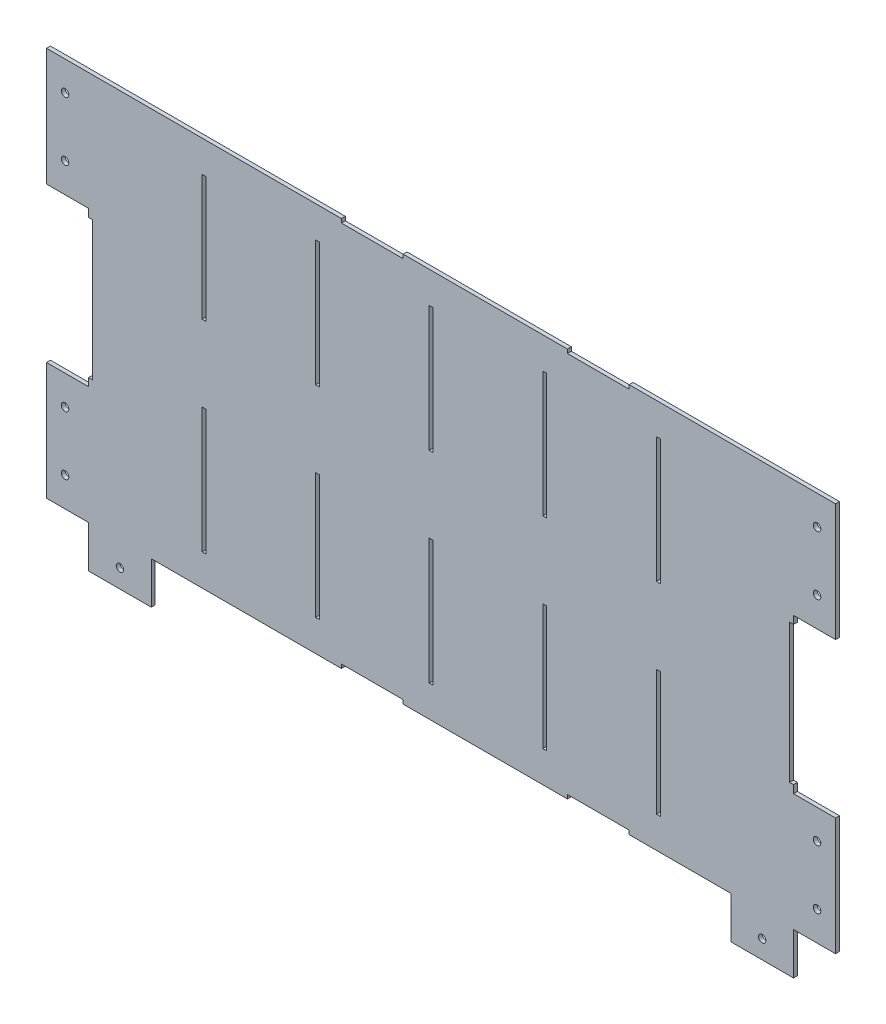
SolidWorks part; units mm, degrees
material "6061-T6 (SS)"
ref_plane "X-Y Datum" through (0, 0, 0) normal (0, 0, 1) x (1, 0, 0)
ref_plane "X-Z Datum" through (0, 0, 0) normal (0, 1, 0) x (1, 0, 0)
ref_plane "Y-Z Datum" through (0, 0, 0) normal (1, 0, 0) x (0, 0, -1)
sketch "Sketch1" plane through (0, 0, 0) normal (0, 0, 1) x (1, 0, 0)
  line L0 (-285.4305, 0) -> (285.4305, 0) construction
  line L1 (-285.4305, -157.7875) -> (285.4305, -157.7875)
  line L2 (-285.4305, -157.7875) -> (-285.4305, 157.7875)
  line L3 (-285.4305, 157.7875) -> (285.4305, 157.7875)
  line L4 (285.4305, -157.7875) -> (285.4305, 157.7875)
  line L5 (-285.4305, -157.7875) -> (285.4305, 157.7875) construction
  line L6 (-285.4305, 157.7875) -> (285.4305, -157.7875) construction
  line L7 (-282.2555, -154.615) -> (-282.2555, 154.615)
  line L8 (-280.6655, -153.025) -> (-195.0655, -153.025)
  line L9 (-280.6655, -153.025) -> (-280.6655, 153.025)
  line L10 (-280.6655, 153.025) -> (-195.0655, 153.025)
  line L11 (-195.0655, -153.025) -> (-195.0655, 153.025)
  line L12 (-280.6655, -153.025) -> (-195.0655, 153.025) construction
  line L13 (-280.6655, 153.025) -> (-195.0655, -153.025) construction
  line L14 (-282.2555, 154.615) -> (-193.4755, 154.615)
  line L15 (-193.4755, -154.615) -> (-193.4755, 154.615)
  line L16 (-282.2555, -154.615) -> (-193.4755, -154.615)
  line L17 (-190.3005, 154.615) -> (-101.5205, 154.615)
  line L18 (-188.7105, 153.025) -> (-103.1105, 153.025)
  line L19 (-190.3005, -154.615) -> (-190.3005, 154.615)
  line L20 (-188.7105, -153.025) -> (-188.7105, 153.025)
  line L21 (-101.5205, -154.615) -> (-101.5205, 154.615)
  line L22 (-103.1105, -153.025) -> (-103.1105, 153.025)
  line L23 (-188.7105, -153.025) -> (-103.1105, -153.025)
  line L24 (-190.3005, -154.615) -> (-101.5205, -154.615)
  line L25 (-188.7105, -153.025) -> (-103.1105, 153.025) construction
  line L26 (-188.7105, 153.025) -> (-103.1105, -153.025) construction
  line L27 (-98.3455, 154.615) -> (-9.5655, 154.615)
  line L28 (-96.7555, 153.025) -> (-11.1555, 153.025)
  line L29 (-98.3455, -154.615) -> (-98.3455, 154.615)
  line L30 (-96.7555, -153.025) -> (-96.7555, 153.025)
  line L31 (-9.5655, -154.615) -> (-9.5655, 154.615)
  line L32 (-11.1555, -153.025) -> (-11.1555, 153.025)
  line L33 (-96.7555, -153.025) -> (-11.1555, -153.025)
  line L34 (-98.3455, -154.615) -> (-9.5655, -154.615)
  line L35 (-96.7555, -153.025) -> (-11.1555, 153.025) construction
  line L36 (-96.7555, 153.025) -> (-11.1555, -153.025) construction
  line L37 (-6.3905, 154.615) -> (82.3895, 154.615)
  line L38 (-4.8005, 153.025) -> (80.7995, 153.025)
  line L39 (-6.3905, -154.615) -> (-6.3905, 154.615)
  line L40 (-4.8005, -153.025) -> (-4.8005, 153.025)
  line L41 (82.3895, -154.615) -> (82.3895, 154.615)
  line L42 (80.7995, -153.025) -> (80.7995, 153.025)
  line L43 (-4.8005, -153.025) -> (80.7995, -153.025)
  line L44 (-6.3905, -154.615) -> (82.3895, -154.615)
  line L45 (-4.8005, -153.025) -> (80.7995, 153.025) construction
  line L46 (-4.8005, 153.025) -> (80.7995, -153.025) construction
  line L47 (85.5645, 154.615) -> (174.3445, 154.615)
  line L48 (87.1545, 153.025) -> (172.7545, 153.025)
  line L49 (85.5645, -154.615) -> (85.5645, 154.615)
  line L50 (87.1545, -153.025) -> (87.1545, 153.025)
  line L51 (174.3445, -154.615) -> (174.3445, 154.615)
  line L52 (172.7545, -153.025) -> (172.7545, 153.025)
  line L53 (87.1545, -153.025) -> (172.7545, -153.025)
  line L54 (85.5645, -154.615) -> (174.3445, -154.615)
  line L55 (87.1545, -153.025) -> (172.7545, 153.025) construction
  line L56 (87.1545, 153.025) -> (172.7545, -153.025) construction
  point P0 (0, 0)
  point P8 (-237.8655, 0)
  point P17 (-145.9105, 0)
  dimension "D1" = 570.861
  dimension "D2" = 315.575
  dimension "D3" = 306.05
  dimension "D4" = 85.6
  dimension "D5" = 3.175
  dimension "D8" = 3.175
  dimension "D9" = 91.955
  dimension "D6" = 1.59
  dimension "D7" = 5
extrude "Boss-Extrude1" add sketch "Sketch1" along normal blind 3.175
sketch "Sketch2" plane through (0, 0, 3.175) normal (0, 0, 1) x (1, 0, 0)
  line L0 (-190.3005, -154.615) -> (-193.4755, -154.615) construction
  line L1 (-191.888, -154.615) -> (-191.888, 157.7875) construction
  line L2 (-285.4305, 157.7875) -> (285.4305, 157.7875) construction
  line L4 (-193.4755, -30.7875) -> (-190.3005, -30.7875)
  line L5 (-193.4755, -30.7875) -> (-193.4755, -132.3875)
  line L6 (-193.4755, -132.3875) -> (-190.3005, -132.3875)
  line L7 (-190.3005, -30.7875) -> (-190.3005, -132.3875)
  line L8 (-193.4755, -30.7875) -> (-190.3005, -132.3875) construction
  line L9 (-193.4755, -132.3875) -> (-190.3005, -30.7875) construction
  line L12 (-285.4305, -157.7875) -> (285.4305, -157.7875) construction
  point P8 (-191.888, -81.5875)
  dimension "D1" = 76.2
  dimension "D2" = 3.175
  dimension "D3" = 101.6
extrude "Cut-Extrude1" cut sketch "Sketch2" against normal blind 3.175
sketch "Sketch7" plane through (0, 0, 3.175) normal (0, 0, 1) x (1, 0, 0)
  line L0 (285.4305, -157.7875) -> (285.4305, 157.7875) construction
  line L1 (102.3049, -154.6125) -> (152.3049, -154.6125)
  line L2 (102.3049, -154.6125) -> (102.3049, -157.7875)
  line L3 (102.3049, -157.7875) -> (152.3049, -157.7875)
  line L4 (152.3049, -154.6125) -> (152.3049, -157.7875)
  line L5 (-80.6951, -154.6125) -> (-30.6951, -154.6125)
  line L6 (-80.6951, -154.6125) -> (-80.6951, -157.7875)
  line L7 (-80.6951, -157.7875) -> (-30.6951, -157.7875)
  line L8 (-30.6951, -154.6125) -> (-30.6951, -157.7875)
  dimension "D1" = 133
  dimension "D2" = 50
  dimension "D3" = 3.175
  dimension "D4" = 50
  dimension "D5" = 133.1256
extrude "Cut-Extrude5" cut sketch "Sketch7" against normal blind 3.175
mirror "Mirror3" about plane through (0, 0, 0) normal (0, 1, 0) of "Cut-Extrude1"
pattern_linear "LPattern2" count 5 spacing 91.96 along (1, 0, 0) of "Mirror3", "Cut-Extrude1"
sketch "Sketch9" plane through (0, 0, 0) normal (0, 0, -1) x (-1, 0, 0)
  line L0 (-304.4805, -62.5375) -> (-304.4805, -157.7875) construction
  line L9 (-285.4305, 157.7875) -> (-190.3024, 157.7875)
  line L10 (-285.4305, 157.7875) -> (-285.4305, 191.8235)
  line L11 (-285.4305, 191.8235) -> (-190.3024, 191.8235)
  line L12 (-190.3024, 157.7875) -> (-190.3024, 191.8235)
  line L13 (-285.4305, 157.7875) -> (-323.5305, 157.7875)
  line L14 (-285.4305, 157.7875) -> (-285.4305, 62.5375)
  line L15 (-285.4305, 62.5375) -> (-323.5305, 62.5375)
  line L18 (-323.5305, 110.1625) -> (-285.4305, 110.1625) construction
  line L20 (-285.4305, -157.7875) -> (-323.5305, -157.7875)
  line L26 (-285.4305, -62.5375) -> (-323.5305, -62.5375)
  line L28 (-323.5305, -106.9875) -> (-323.5305, -157.7875) construction
  line L29 (-323.5305, -106.9875) -> (-285.4305, -106.9875) construction
  line L30 (-304.4805, -62.5375) -> (-304.4805, -110.1625) construction
  line L31 (-304.4805, -110.1625) -> (-304.4805, -157.7875) construction
  line L32 (-304.4805, -62.5375) -> (-304.4805, -110.1625) construction
  line L33 (-304.4805, -110.1625) -> (-304.4805, -157.7875) construction
  line L35 (-323.5305, 62.5375) -> (-323.5305, 157.7875) construction
  line L36 (-319.4665, 157.7875) -> (-319.4665, 62.5375)
  line L37 (-323.5305, -62.5375) -> (-323.5305, -157.7875) construction
  line L40 (-304.4805, 157.7875) -> (-304.4805, 110.1625) construction
  line L41 (-304.4805, 110.1625) -> (-304.4805, 62.5375) construction
  line L42 (-319.4665, -62.5375) -> (-319.4665, -157.7875)
  line L43 (-304.4805, 110.1625) -> (-304.4805, 62.5375) construction
  line L44 (-304.4805, -62.5375) -> (-304.4805, -110.1625) construction
  line L45 (-304.4805, -110.1625) -> (-304.4805, -157.7875) construction
  line L46 (-285.4305, -62.5375) -> (-285.4305, -157.7875)
  line L47 (-285.4305, 176.8375) -> (-190.3024, 176.8375) construction
  line L48 (-285.4305, 176.8375) -> (-260.0305, 176.8375) construction
  line L49 (-234.6305, 191.8235) -> (-234.6305, 157.7875) construction
  line L50 (-285.4305, -176.8375) -> (-234.6305, -176.8375) construction
  line L51 (-285.4305, -157.7875) -> (-234.6305, -157.7875)
  line L52 (-285.4305, -157.7875) -> (-285.4305, -191.7755)
  line L53 (-285.4305, -191.7755) -> (-234.6305, -191.7755)
  line L54 (-234.6305, -157.7875) -> (-234.6305, -191.7755)
  circle A4 centre (-304.4805, 133.975) radius 3.048
  circle A6 centre (-304.4805, 86.35) radius 3.048
  circle A7 centre (-304.4805, -86.35) radius 3.048
  circle A8 centre (-304.4805, -133.975) radius 3.048
  circle A10 centre (-260.0305, 176.8375) radius 3.048
  circle A11 centre (-260.0305, -176.8375) radius 3
  point P22 (-307.5285, 133.975)
  point P39 (-260.0305, 179.8855)
  point P50 (-260.0305, -179.8375)
  dimension "D1" = 11.938
  dimension "D2" = 95.25
  dimension "D6" = 6.096
  dimension "D7" = 95.25
  dimension "D8" = 6.096
  dimension "D9" = 6.096
  dimension "D10" = 6.096
  dimension "D12" = 19.05
  dimension "D13" = 11.938
  dimension "D11" = 25.4
  dimension "D15" = 6
  dimension "D3" = 95.1281
  dimension "D4" = 34.036
  dimension "D5" = 19.05
  dimension "D14" = 25.4
  dimension "D16" = 19.05
  dimension "D17" = 11.938
  dimension "D18" = 50.8
  dimension "D19" = 25.4
extrude "Boss-Extrude3" add sketch "Sketch9" against normal blind 3.175
mirror "Mirror4" about plane through (0, 0, 0) normal (1, 0, 0) of "Boss-Extrude3"
mirror "Mirror5" about plane through (0, 0, 0) normal (0, 1, 0) of "Cut-Extrude5"
sketch "Sketch10" plane through (0, 0, 0) normal (0, 0, -1) x (-1, 0, 0)
  line L0 (-285.4305, 62.5375) -> (-285.4305, 56.1875)
  line L1 (-285.4305, -62.5375) -> (-285.4305, 62.5375) construction
  line L2 (-285.4305, -62.5375) -> (-319.4665, -62.5375) construction
  line L3 (-285.4305, 56.1875) -> (-282.2555, 56.1875)
  line L4 (-285.4305, 56.1875) -> (-285.4305, -56.1875)
  line L5 (-285.4305, -56.1875) -> (-282.2555, -56.1875)
  line L6 (-282.2555, 56.1875) -> (-282.2555, -56.1875)
  line L7 (-285.4305, 62.5375) -> (-319.4665, 62.5375) construction
  dimension "D1" = 6.35
  dimension "D2" = 3.175
  dimension "D3" = 6.35
extrude "Cut-Extrude6" cut sketch "Sketch10" against normal through all contours L6 L3 L4 L5
mirror "Mirror6" about plane through (0, 0, 0) normal (1, 0, 0) of "Cut-Extrude6"
